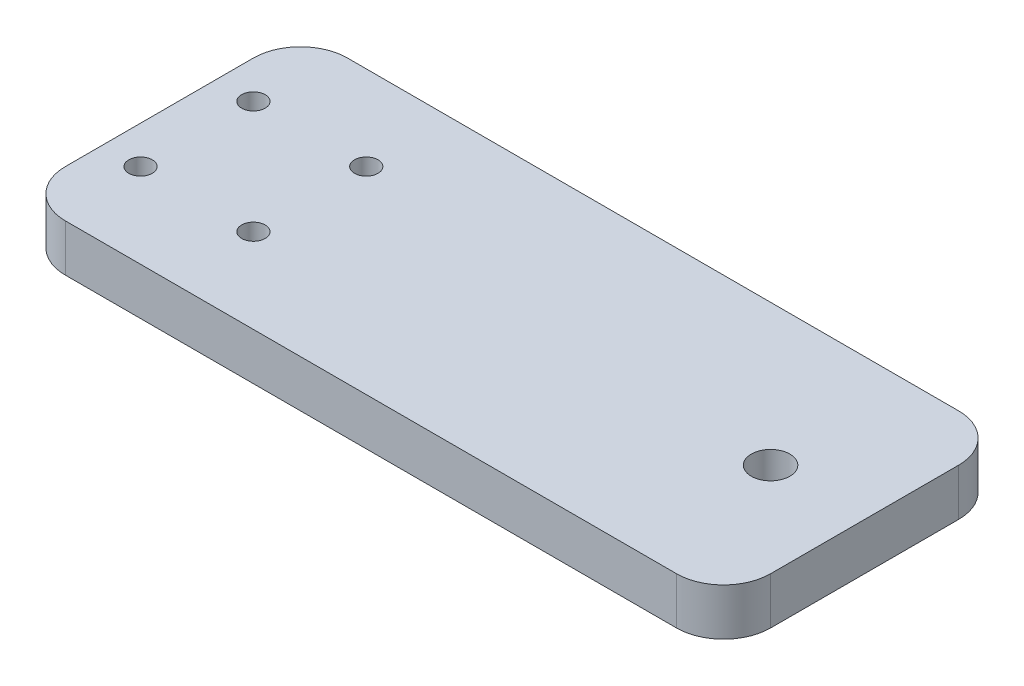
SolidWorks part; units mm, degrees
ref_plane "正面" through (0, 0, 0) normal (0, 0, 1) x (1, 0, 0)
ref_plane "平面" through (0, 0, 0) normal (0, 1, 0) x (1, 0, 0)
ref_plane "右側面" through (0, 0, 0) normal (1, 0, 0) x (0, 0, -1)
sketch "ｽｹｯﾁ1" plane through (0, 0, 0) normal (0, 1, 0) x (1, 0, 0)
  line L1 (-75, -30) -> (75, -30)
  line L2 (-75, -30) -> (-75, 30)
  line L3 (-75, 30) -> (75, 30)
  line L4 (75, -30) -> (75, 30)
  line L5 (-75, -30) -> (75, 30) construction
  line L6 (-75, 30) -> (75, -30) construction
  point P0 (0, 0)
  dimension "D1" = 60
  dimension "D2" = 150
extrude "ﾎﾞｽ - 押し出し1" add sketch "ｽｹｯﾁ1" along normal blind 10
fillet "ﾌｨﾚｯﾄ1" radius 10 4 edges at (-75, 5, -30) (75, 5, -30) (75, 5, 30) (-75, 5, 30)
sketch "ｽｹｯﾁ2" plane through (0, 10, 0) normal (0, 1, 0) x (1, 0, 0)
  line L0 (-55, 0) -> (55, 0) construction
  line L1 (-75, 20) -> (-75, -20) construction
  circle A0 centre (-67, 12) radius 2.5
  circle A1 centre (-43, 12) radius 2.5
  circle A2 centre (-67, -12) radius 2.5
  circle A3 centre (-43, -12) radius 2.5
  circle A4 centre (55, 0) radius 4.1
  dimension "D3" = 5
  dimension "D8" = 8.2
  dimension "D1" = 110
  dimension "D2" = 20
  dimension "D4" = 24
  dimension "D5" = 24
  dimension "D6" = 12
  dimension "D7" = 12
extrude "ｶｯﾄ - 押し出し1" cut sketch "ｽｹｯﾁ2" against normal through all
